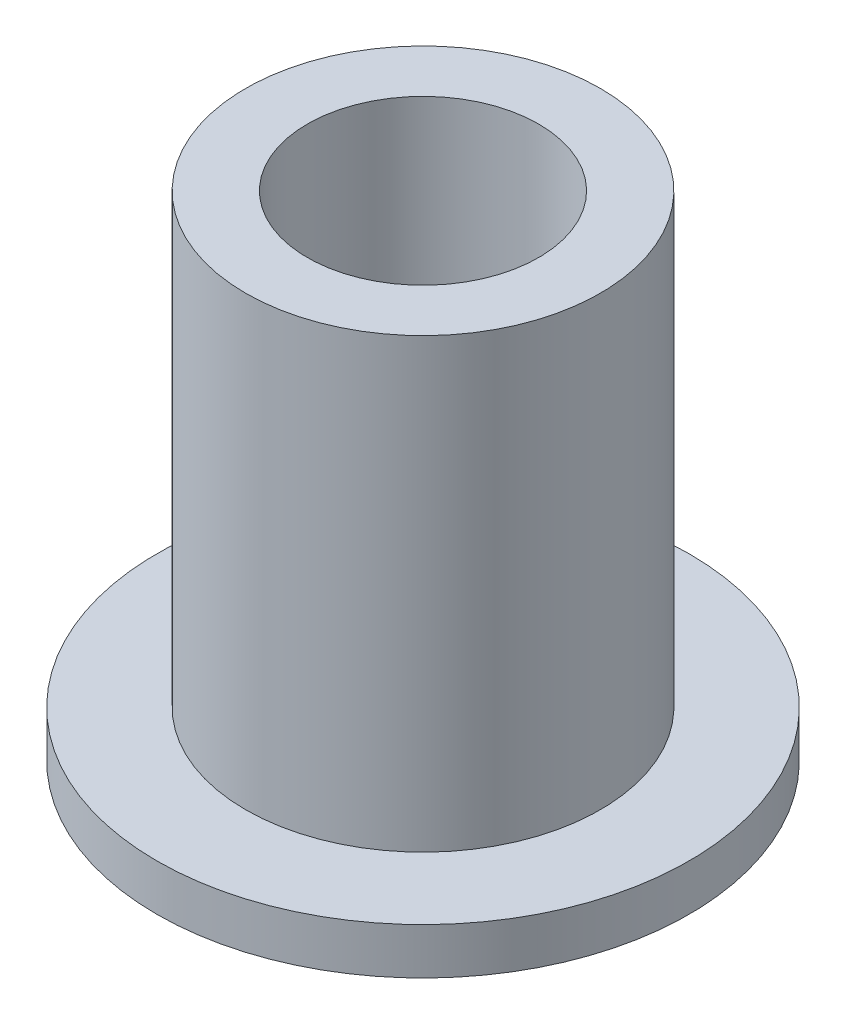
SolidWorks part; units mm, degrees
ref_plane "Front Plane" through (0, 0, 0) normal (0, 0, 1) x (1, 0, 0)
ref_plane "Top Plane" through (0, 0, 0) normal (0, 1, 0) x (1, 0, 0)
ref_plane "Right Plane" through (0, 0, 0) normal (1, 0, 0) x (0, 0, -1)
sketch "Sketch1" plane through (0, 0, 0) normal (0, 0, 1) x (1, 0, 0)
  line L0 (0, 0) -> (0, 6.4) construction
  line L1 (1.5, 0) -> (3.45, 0)
  line L2 (3.45, 0) -> (3.45, 0.6)
  line L3 (3.45, 0.6) -> (2.3, 0.6)
  line L4 (2.3, 0.6) -> (2.3, 6.4)
  line L5 (2.3, 6.4) -> (1.5, 6.4)
  line L6 (1.5, 6.4) -> (1.5, 0)
  dimension "D1" = 3.45
  dimension "D2" = 6.4
  dimension "D3" = 1.5
  dimension "D4" = 2.3
  dimension "D5" = 0.6
revolve "Revolve1" add sketch "Sketch1" angle 360 about L0
